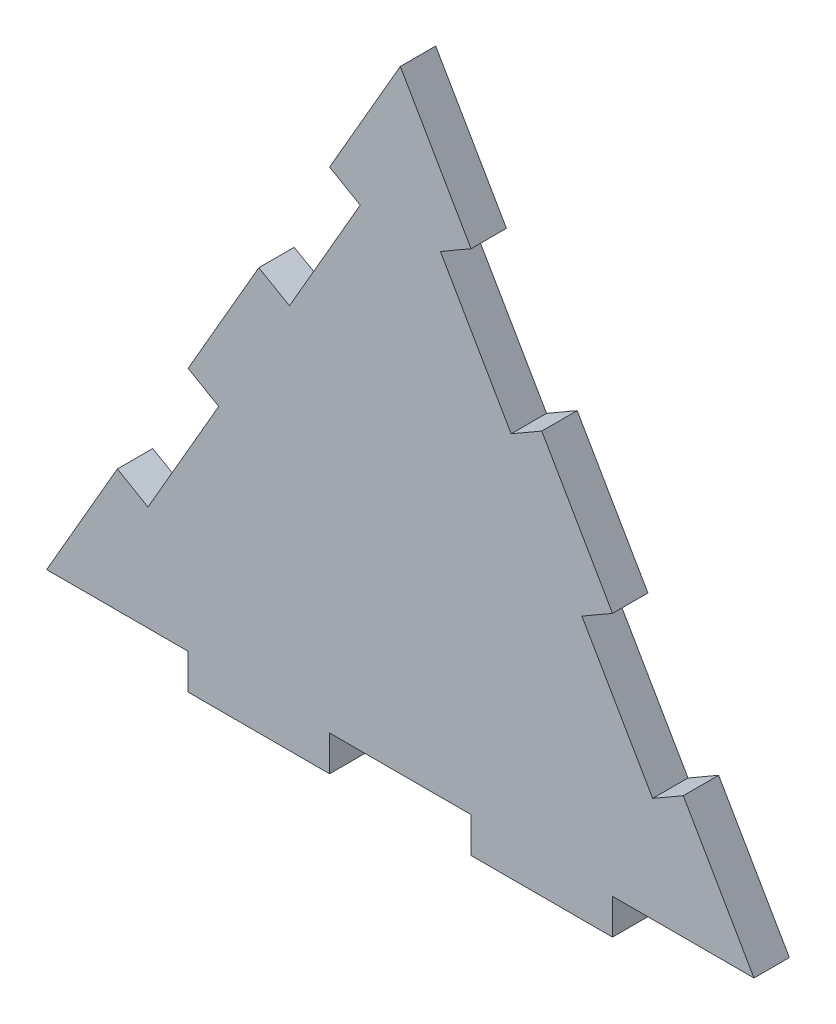
SolidWorks part; units mm, degrees
ref_plane "Front Plane" through (0, 0, 0) normal (0, 0, 1) x (1, 0, 0)
ref_plane "Top Plane" through (0, 0, 0) normal (0, 1, 0) x (1, 0, 0)
ref_plane "Right Plane" through (0, 0, 0) normal (1, 0, 0) x (0, 0, -1)
sketch "Esquisse1" plane through (0, 0, 0) normal (0, 0, 1) x (1, 0, 0)
  line L0 (0, 0) -> (-100, 0)
  line L1 (-100, 0) -> (-50, 86.6025)
  line L2 (-50, 86.6025) -> (0, 0)
  dimension "D1" = 100
extrude "Boss.-Extru.1" add sketch "Esquisse1" along normal blind 5
sketch "Esquisse2" plane through (0, 0, 0) normal (0, 0, -1) x (-1, 0, 0)
  line L0 (100, 0) -> (0, 0) construction
  line L1 (20, 0) -> (40, 0)
  line L2 (20, 0) -> (20, -5)
  line L3 (20, -5) -> (40, -5)
  line L4 (40, 0) -> (40, -5)
  line L5 (30, -5) -> (30, 0) construction
  line L6 (20, -2.5) -> (40, -2.5) construction
  line L7 (100, -5) -> (80, -5) construction
  line L9 (60, 0) -> (80, 0)
  line L10 (60, 0) -> (60, -5)
  line L11 (60, -5) -> (80, -5)
  line L12 (80, 0) -> (80, -5)
  line L13 (70, -5) -> (70, 0) construction
  line L14 (60, -2.5) -> (80, -2.5) construction
  point P104 (30, -2.5)
  point P133 (70, -2.5)
  dimension "D1" = 20
  dimension "D2" = 20
  dimension "D3" = 20
  dimension "D4" = 20
extrude "Boss.-Extru.2" add sketch "Esquisse2" against normal blind 5
sketch "Esquisse3" plane through (0, 0, 5) normal (0, 0, 1) x (1, 0, 0)
  line L0 (-60, 69.282) -> (-55.6699, 66.782)
  line L1 (-50, 86.6025) -> (-100, 0) construction
  line L2 (-55.6699, 66.782) -> (-60, 69.282) construction
  line L3 (-55.6699, 66.782) -> (-65.6699, 49.4615)
  line L4 (-65.6699, 49.4615) -> (-70, 51.9615)
  line L5 (-65.6699, 49.4615) -> (-70, 51.9615) construction
  line L6 (-70, 51.9615) -> (-60, 69.282)
  line L7 (-80, 34.641) -> (-75.6699, 32.141)
  line L8 (-75.6699, 32.141) -> (-80, 34.641) construction
  line L9 (-75.6699, 32.141) -> (-85.6699, 14.8205)
  line L10 (-85.6699, 14.8205) -> (-90, 17.3205)
  line L11 (-85.6699, 14.8205) -> (-90, 17.3205) construction
  line L12 (-90, 17.3205) -> (-80, 34.641)
  line L13 (-50, 86.6025) -> (-50, 0) construction
  line L14 (-60, 0) -> (-40, 0) construction
  line L15 (-10, 17.3205) -> (-20, 34.641)
  line L16 (-14.3301, 14.8205) -> (-10, 17.3205)
  line L17 (-24.3301, 32.141) -> (-14.3301, 14.8205)
  line L18 (-20, 34.641) -> (-24.3301, 32.141)
  line L19 (-30, 51.9615) -> (-40, 69.282)
  line L20 (-34.3301, 49.4615) -> (-30, 51.9615)
  line L21 (-44.3301, 66.782) -> (-34.3301, 49.4615)
  line L22 (-40, 69.282) -> (-44.3301, 66.782)
extrude "Enlèv. mat.-Extru.1" cut sketch "Esquisse3" against normal through all
